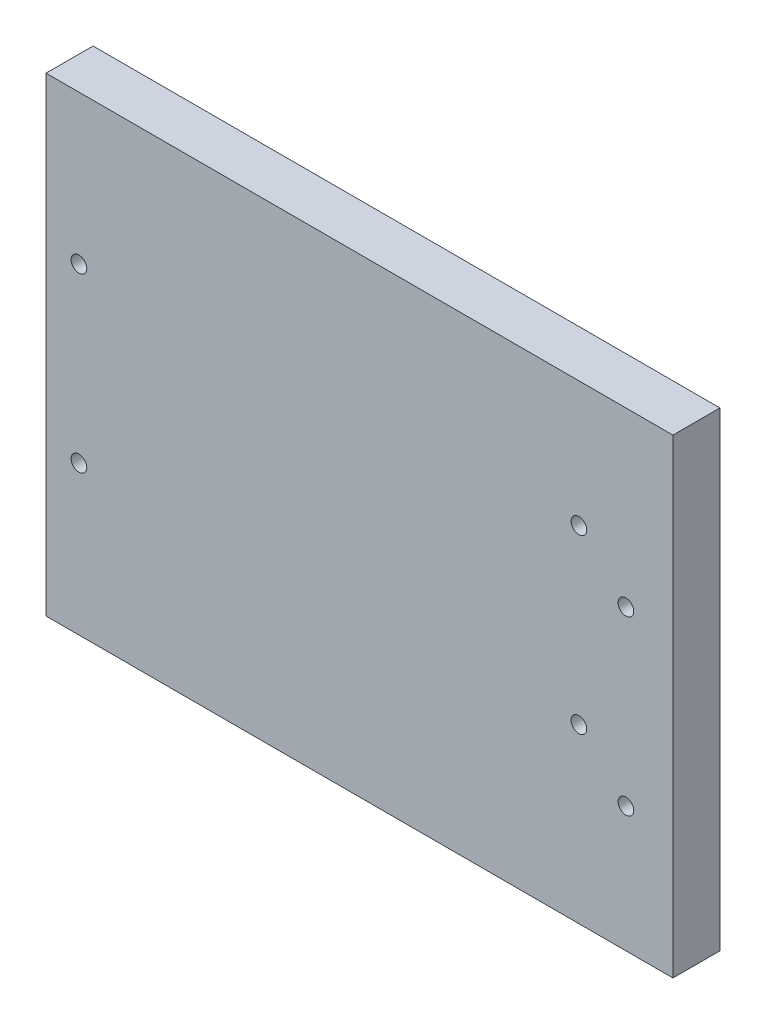
SolidWorks part; units mm, degrees
material "Pine"
ref_plane "Front Plane" through (0, 0, 0) normal (0, 0, 1) x (1, 0, 0)
ref_plane "Top Plane" through (0, 0, 0) normal (0, 1, 0) x (1, 0, 0)
ref_plane "Right Plane" through (0, 0, 0) normal (1, 0, 0) x (0, 0, -1)
sketch "Sketch1" plane through (0, 0, 0) normal (0, 0, 1) x (1, 0, 0)
  line L1 (100, -75) -> (-100, -75)
  line L2 (100, -75) -> (100, 75)
  line L3 (100, 75) -> (-100, 75)
  line L4 (-100, -75) -> (-100, 75)
  line L5 (100, -75) -> (-100, 75) construction
  line L6 (100, 75) -> (-100, -75) construction
  point P0 (0, 0)
  dimension "D1" = 200
  dimension "D2" = 150
extrude "Boss-Extrude1" add sketch "Sketch1" along normal blind 15
sketch "Sketch2" plane through (0, 0, 15) normal (0, 0, 1) x (1, 0, 0)
  line L0 (100, -75) -> (100, 75) construction
  line L1 (-100, -75) -> (100, -75) construction
  line L2 (100, 75) -> (-100, 75) construction
  line L3 (-100, 75) -> (-100, -75) construction
  circle A0 centre (85, -35) radius 2.5
  circle A1 centre (70, -20) radius 2.5
  circle A2 centre (85, 20) radius 2.5
  circle A3 centre (70, 35) radius 2.5
  circle A4 centre (-89.5, 27.5) radius 2.5
  circle A5 centre (-89.5, -27.5) radius 2.5
  dimension "D1" = 5
  dimension "D2" = 5
  dimension "D3" = 5
  dimension "D4" = 5
  dimension "D5" = 5
  dimension "D6" = 5
  dimension "D7" = 15
  dimension "D8" = 15
  dimension "D9" = 30
  dimension "D10" = 30
  dimension "D11" = 40
  dimension "D12" = 55
  dimension "D13" = 40
  dimension "D14" = 55
  dimension "D15" = 47.5
  dimension "D16" = 47.5
  dimension "D17" = 10.5
  dimension "D18" = 10.5
extrude "Cut-Extrude1" cut sketch "Sketch2" against normal through all
sketch "Sketch3" plane through (0, 0, 0) normal (0, 0, -1) x (-1, 0, 0)
  circle A0 centre (-70, 35) radius 5
  circle A2 centre (-85, 20) radius 5
  circle A3 centre (-70, -20) radius 5
  circle A4 centre (-85, -35) radius 5
  circle A5 centre (89.5, -27.5) radius 5
  circle A6 centre (89.5, 27.5) radius 5
extrude "Cut-Extrude2" cut sketch "Sketch3" against normal blind 6
